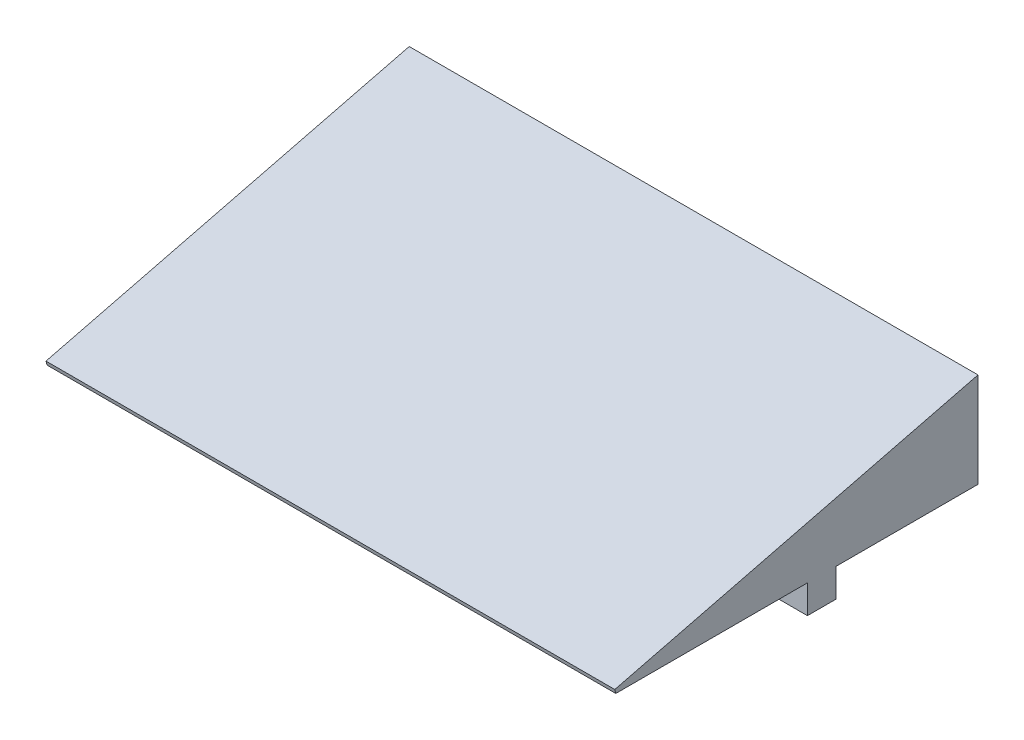
SolidWorks part; units mm, degrees
ref_plane "Front Plane" through (0, 0, 0) normal (0, 0, 1) x (1, 0, 0)
ref_plane "Top Plane" through (0, 0, 0) normal (0, 1, 0) x (1, 0, 0)
ref_plane "Right Plane" through (0, 0, 0) normal (1, 0, 0) x (0, 0, -1)
sketch "Sketch3" plane through (0, 0, 0) normal (0, 1, 0) x (1, 0, 0)
  line L1 (-60, 40) -> (60, 40)
  line L2 (-60, 40) -> (-60, -40)
  line L3 (-60, -40) -> (60, -40)
  line L4 (60, 40) -> (60, -40)
  line L5 (-60, 40) -> (60, -40) construction
  line L6 (-60, -40) -> (60, 40) construction
  point P0 (0, 0)
  dimension "D1" = 120
  dimension "D2" = 80
extrude "Boss-Extrude1" add sketch "Sketch3" along normal blind 20
sketch "Sketch4" plane through (60, 0, 0) normal (1, 0, 0) x (0, 0, -1)
  line L2 (-40, 0) -> (40, 0)
  line L3 (-39.9714, 0) -> (40, 20)
  line L4 (-38.6975, 0) -> (40, 0)
  line M4 (-40, 0) -> (40, 0)
  line M6 (40, 20) -> (-40, 20)
  line M7 (-40, 20) -> (-40, 0)
extrude "Cut-Extrude3" cut sketch "Sketch4" against normal blind 120 and the other way through all contours L3 M4 M6 M7
sketch "Sketch5" plane through (60, 0, 0) normal (1, 0, 0) x (0, 0, -1)
  line L0 (4.0143, 0) -> (4.0143, -6)
  line L1 (-39.9714, 0) -> (40, 0) construction
  line L2 (4.0143, -6) -> (10.0143, -6)
  line L3 (10.0143, -6) -> (10.0143, 0)
  line L4 (-39.9714, 0) -> (4.0143, 0)
  line L5 (4.0143, 0) -> (10.0143, 0)
  line L7 (40, 20) -> (-39.9714, 0)
  line L8 (-39.9714, 0) -> (40, 0)
  line L9 (40, 0) -> (40, 20)
  line L10 (40, 20) -> (-39.9714, 0)
  line L11 (10.0143, 0) -> (40, 0)
  line L12 (40, 0) -> (40, 20)
  point P4 (0.0143, 0)
  line M4 (-39.9714, 0) -> (40, 0)
  dimension "D1" = 6
  dimension "D2" = 6
  dimension "D3" = 10
  dimension "D4" = 0
extrude "Boss-Extrude2" add sketch "Sketch5" against normal blind 120 contours L2 L3 L0 M4
sketch "Sketch6" plane through (0, 9.408, 2.3528) normal (0, 0.9701, 0.2426) x (1, 0, 0)
  line L0 (-60, -38.7771) -> (-60, -35.3287)
  line L1 (-60, -38.7771) -> (-60, 43.6572) construction
  line L2 (-60, -35.3287) -> (60, -35.3287)
  line L3 (60, -38.7771) -> (60, 43.6572) construction
  line L4 (60, -35.3287) -> (60, -38.7771)
  line L5 (-60, -38.7771) -> (60, -38.7771) construction
  line L6 (60, -38.7771) -> (-60, -38.7771)
extrude "Cut-Extrude4" cut sketch "Sketch6" against normal blind 10
